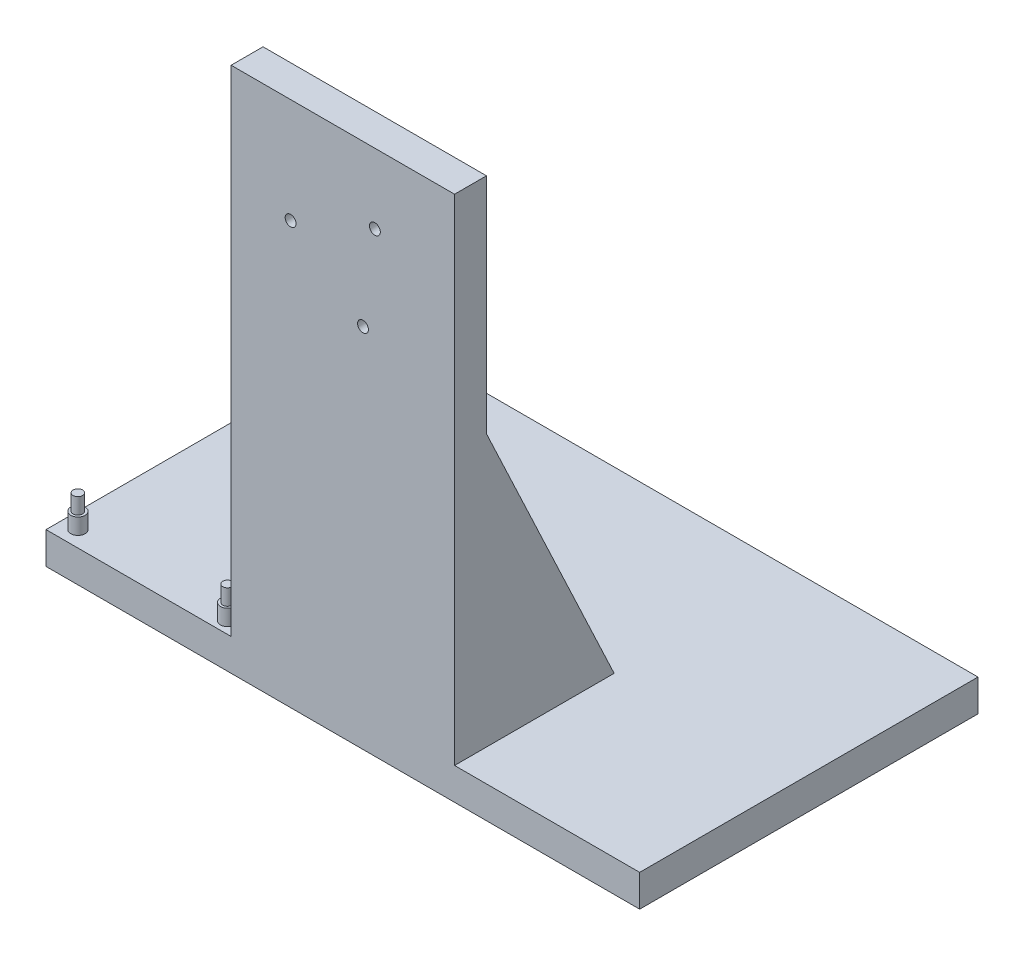
SolidWorks part; units mm, degrees
ref_plane "Front Plane" through (0, 0, 0) normal (0, 0, 1) x (1, 0, 0)
ref_plane "Top Plane" through (0, 0, 0) normal (0, 1, 0) x (1, 0, 0)
ref_plane "Right Plane" through (0, 0, 0) normal (1, 0, 0) x (0, 0, -1)
sketch "Sketch1" plane through (0, 0, 0) normal (0, 0, 1) x (1, 0, 0)
  line L1 (-35, -35) -> (35, -35)
  line L2 (-35, -35) -> (-35, 35)
  line L3 (-35, 35) -> (35, 35)
  line L4 (35, -35) -> (35, 35)
  line L5 (-35, -35) -> (35, 35) construction
  line L6 (-35, 35) -> (35, -35) construction
  point P0 (0, 0)
  dimension "D2" = 70
  dimension "D1" = 70
extrude "Boss-Extrude1" add sketch "Sketch1" along normal blind 10
sketch "Sketch2" plane through (0, 0, 10) normal (0, 0, 1) x (1, 0, 0)
  line L0 (0, 26.65) -> (0, -26.65) construction
  line L5 (-35, 35) -> (35, -35) construction
  line L6 (35, 35) -> (-35, -35) construction
  line L7 (-26.65, 0) -> (26.65, 0) construction
  line L8 (-16.3588, 2.1537) -> (0, 0) construction
  line L9 (10.0446, 13.0903) -> (0, 0) construction
  line L10 (0, 0) -> (6.3143, -15.244) construction
  line L11 (-27, 0) -> (0, 0) construction
  line L12 (0, 0) -> (27, 0) construction
  circle A0 centre (0, 0) radius 26.65 construction
  circle A1 centre (0, 0) radius 16.5 construction
  circle A2 centre (-27, 0) radius 1
  circle A3 centre (27, 0) radius 1
  point P8 (10.0446, 13.0903)
  point P9 (6.3143, -15.244)
  point P10 (-16.3588, 2.1537)
  dimension "D2" = 53.3
  dimension "D3" = 33
  dimension "D6" = 2
  dimension "D1" = 22.5
  dimension "D4" = 120
  dimension "D5" = 120
  dimension "D7" = 27
sketch "Sketch5" plane through (0, 0, 0) normal (0, 0, 1) x (1, 0, 0)
  point P0 (6.3143, -15.244)
  point P3 (10.0446, 13.0903)
  point P6 (-16.3588, 2.1537)
hole_wizard "CBORE for M3 SHCS1" positions "Sketch5" profile "Sketch4" counterbore size "M3" standard "ANSI Metric" end condition up to next
sketch "Sketch4" plane through (6.3143, -15.244, 0) normal (1, 0, 0) x (0, 1, 0)
  line L0 (0, 0) -> (0, 10)
  line L1 (0, 10) -> (1.7, 10)
  line L3 (1.7, 10) -> (1.7, 3)
  line L4 (3.25, 3) -> (1.7, 3)
  line L5 (3.25, 3) -> (3.25, 0.025)
  line L6 (3.25, 0.025) -> (3.275, 0)
  line L7 (3.275, 0) -> (0, 0)
  line L8 (-3.25, 0.025) -> (-3.275, 0) construction
  line L11 (0, -6.35) -> (0, 107.95) construction
  dimension "Thru Hole Dia." = 3.4
  dimension "Thru Hole Depth" = 10
  dimension "C'Bore Dia." = 6.5
  dimension "C'Bore Depth" = 3
  dimension "Near C'Sink Dia." = 6.55
  dimension "Near C'Sink Angle" = 90
sketch "Sketch14" plane through (0, -35, 0) normal (0, -1, 0) x (1, 0, 0)
  line L1 (-35, 10) -> (35, 10)
  line L2 (-35, 10) -> (-35, 0)
  line L3 (-35, 0) -> (35, 0)
  line L4 (35, 10) -> (35, 0)
extrude "Boss-Extrude2" add sketch "Sketch14" along normal blind 95
sketch "Sketch13" plane through (0, -130, 0) normal (0, -1, 0) x (1, 0, 0)
  line L1 (-93, 10) -> (93, 10)
  line L2 (-93, 10) -> (-93, -96)
  line L3 (-93, -96) -> (93, -96)
  line L4 (93, 10) -> (93, -96)
  line L5 (35, 10) -> (-35, 10) construction
  point P5 (0, 10)
  dimension "D1" = 186
  dimension "D2" = 106
extrude "Boss-Extrude3" add sketch "Sketch13" against normal blind 10 contours L3 L4 L1 L2
chamfer "Chamfer1" distance 40 distance2 85 1 edges at (0, -120, 0)
sketch "Sketch18" plane through (0, -120, -115) normal (0, 1, 0) x (1, 0, 0)
  line L0 (-88, -45.1) -> (-88, -120) construction
  line L1 (-93, -125) -> (-35, -125) construction
  line L2 (-93, -125) -> (-93, -19) construction
  circle A0 centre (-88, -45.1) radius 2.25
  circle A1 centre (-44.9, -69.2) radius 2.25
  circle A2 centre (-72.8, -69.2) radius 2.25
  circle A3 centre (-88, -120) radius 2.25
  circle A4 centre (-39.8, -121.3) radius 2.25
  point P0 (-88, -120)
  point P2 (-88, -45.1)
  point P6 (-39.8, -121.3)
  point P8 (-72.8, -69.2)
  point P10 (-44.9, -69.2)
  dimension "D9" = 4.5
  dimension "D1" = 74.9
  dimension "D2" = 1.3
  dimension "D3" = 15.2
  dimension "D4" = 50.8
  dimension "D5" = 5
  dimension "D6" = 27.9
  dimension "D7" = 5.1
  dimension "D8" = 5
extrude "Boss-Extrude4" add sketch "Sketch18" along normal blind 5
sketch "Sketch19" plane through (0, -115, 0) normal (0, 1, 0) x (1, 0, 0)
  circle A0 centre (-88, 69.9) radius 1.5
  circle A1 centre (-72.8, 45.8) radius 1.5
  circle A2 centre (-44.9, 45.8) radius 1.5
  circle A3 centre (-88, -5) radius 1.5
  circle A4 centre (-39.8, -6.3) radius 1.5
  dimension "D1" = 3
extrude "Boss-Extrude5" add sketch "Sketch19" along normal blind 5
